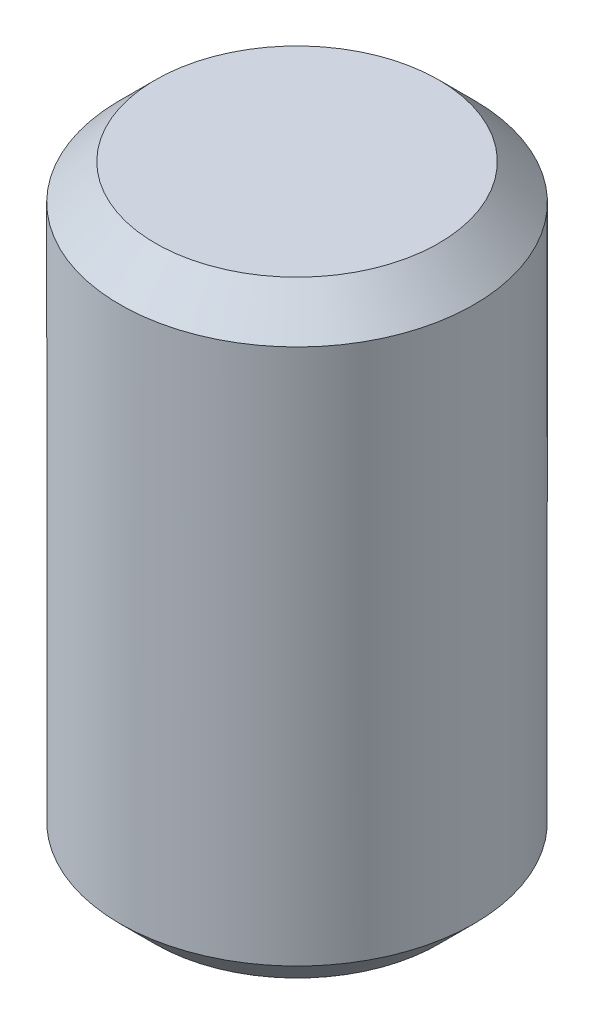
SolidWorks part; units mm, degrees
ref_plane "Front Plane" through (0, 0, 0) normal (0, 0, 1) x (1, 0, 0)
ref_plane "Top Plane" through (0, 0, 0) normal (0, 1, 0) x (1, 0, 0)
ref_plane "Right Plane" through (0, 0, 0) normal (1, 0, 0) x (0, 0, -1)
sketch "Sketch1" plane through (0, 0, 0) normal (0, 1, 0) x (1, 0, 0)
  circle A0 centre (0, 0) radius 1.75
  dimension "D1" = 3.5
extrude "Boss-Extrude1" add sketch "Sketch1" along normal blind 6
chamfer "Chamfer1" distance 0.35 angle 45 2 edges at (0, 0, 1.75) (0, 6, 1.75)
